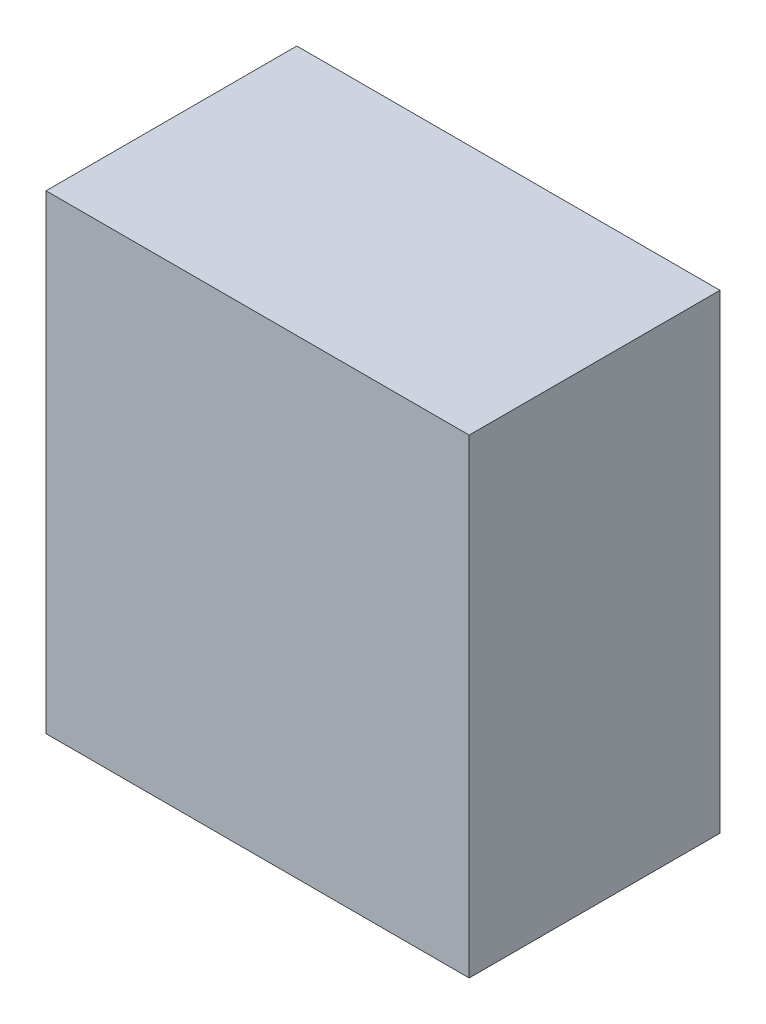
SolidWorks part; units mm, degrees
ref_plane "Front Plane" through (0, 0, 0) normal (0, 0, 1) x (1, 0, 0)
ref_plane "Top Plane" through (0, 0, 0) normal (0, 1, 0) x (1, 0, 0)
ref_plane "Right Plane" through (0, 0, 0) normal (1, 0, 0) x (0, 0, -1)
sketch "Sketch1" plane through (0, 0, 0) normal (0, 1, 0) x (1, 0, 0)
  line L1 (-2.7, -1.6) -> (2.7, -1.6)
  line L2 (-2.7, -1.6) -> (-2.7, 1.6)
  line L3 (-2.7, 1.6) -> (2.7, 1.6)
  line L4 (2.7, -1.6) -> (2.7, 1.6)
  line L5 (-2.7, -1.6) -> (2.7, 1.6) construction
  line L6 (-2.7, 1.6) -> (2.7, -1.6) construction
  point P0 (0, 0)
  dimension "D1" = 5.4
  dimension "D2" = 3.2
extrude "Boss-Extrude1" add sketch "Sketch1" along normal blind 6
